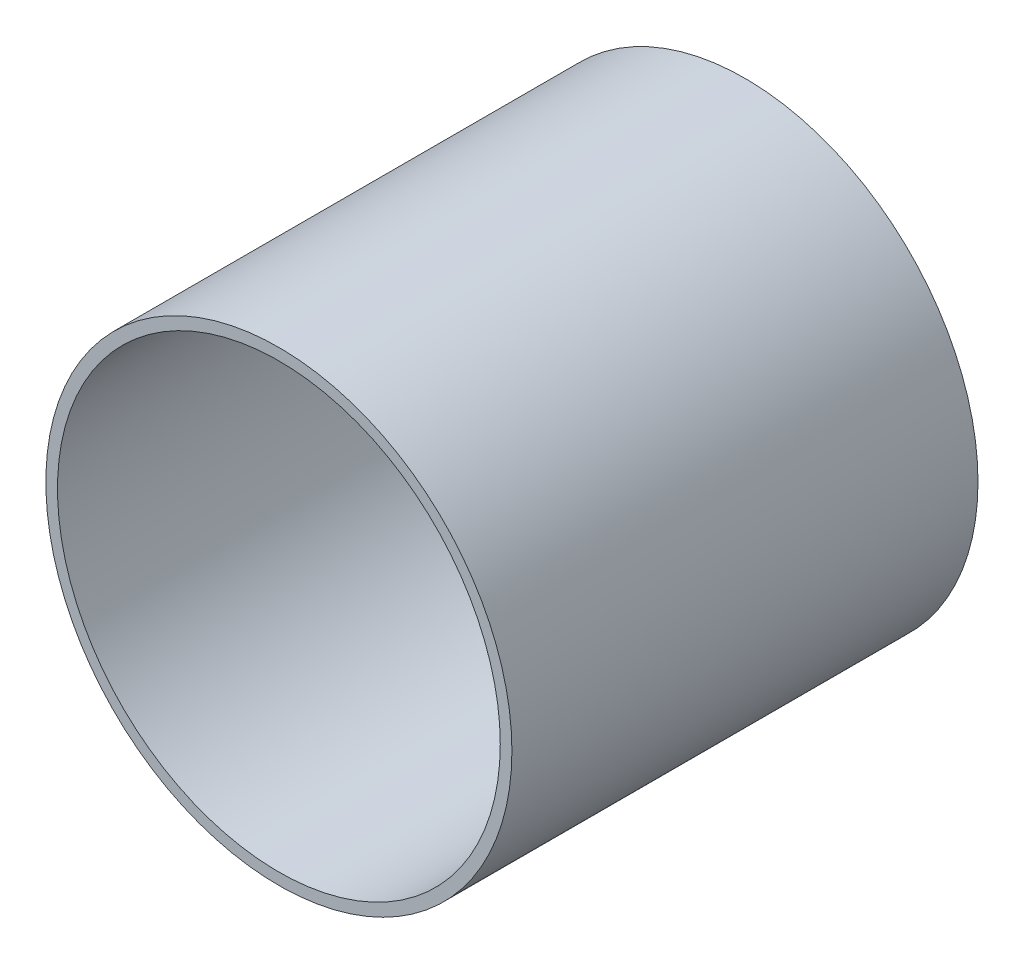
SolidWorks part; units mm, degrees
ref_plane "前视基准面" through (0, 0, 0) normal (0, 0, 1) x (1, 0, 0)
ref_plane "上视基准面" through (0, 0, 0) normal (0, 1, 0) x (1, 0, 0)
ref_plane "右视基准面" through (0, 0, 0) normal (1, 0, 0) x (0, 0, -1)
other "Configuration Table"
sketch "草图2" plane through (0, 0, 0) normal (0, 0, 1) x (1, 0, 0)
  circle A0 centre (0, 0) radius 100
extrude "凸台-拉伸2" add sketch "草图2" along normal blind 200
sketch "草图3" plane through (0, 0, 200) normal (0, 0, 1) x (1, 0, 0)
  circle A0 centre (0, 0) radius 95
extrude "切除-拉伸1" cut sketch "草图3" against normal blind 400
sketch "草图4" plane through (0, 0, 0) normal (0, 0, -1) x (-1, 0, 0)
  circle A0 centre (0, 0) radius 80
extrude "凸台-拉伸3" add sketch "草图4" against normal blind 30 separate body
